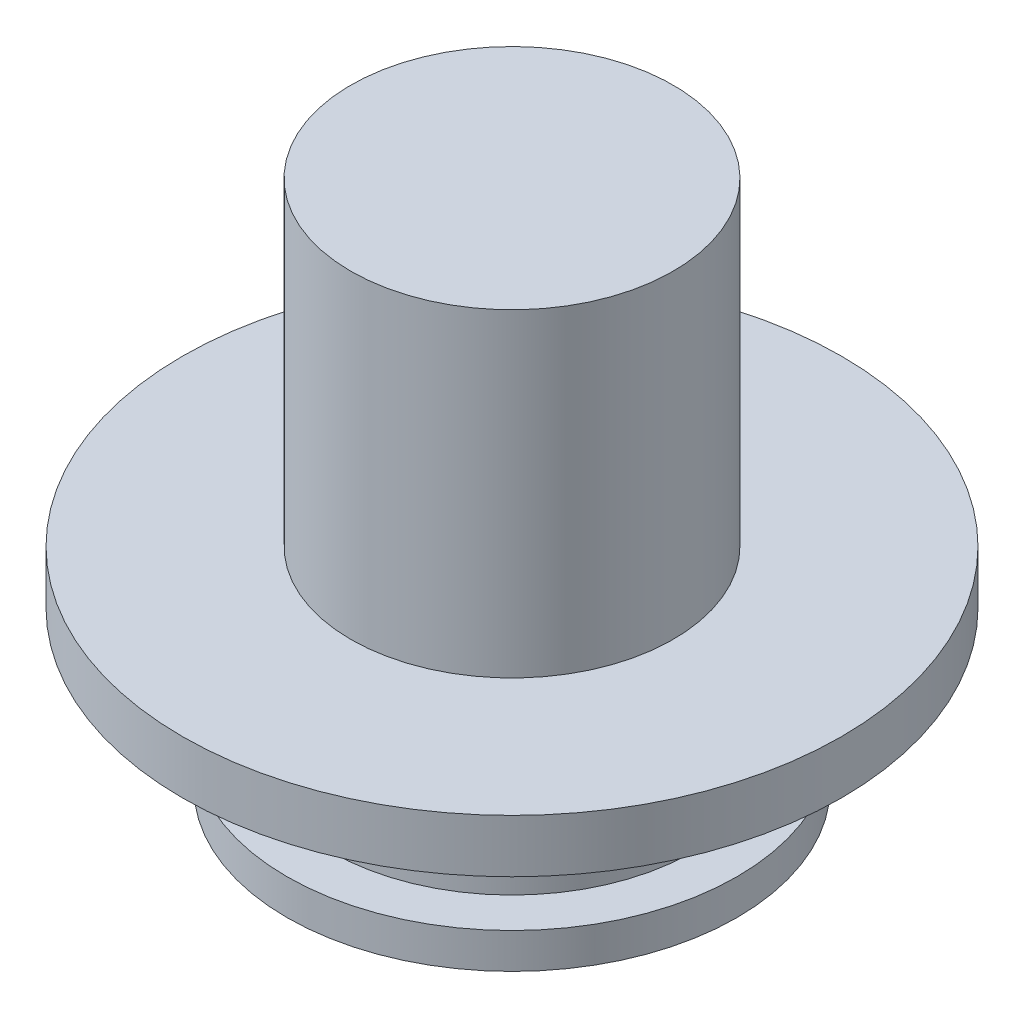
SolidWorks part; units mm, degrees
ref_plane "Front Plane" through (0, 0, 0) normal (0, 0, 1) x (1, 0, 0)
ref_plane "Top Plane" through (0, 0, 0) normal (0, 1, 0) x (1, 0, 0)
ref_plane "Right Plane" through (0, 0, 0) normal (1, 0, 0) x (0, 0, -1)
sketch "Sketch1" plane through (0, 0, 0) normal (0, 1, 0) x (1, 0, 0)
  circle A0 centre (0, 0) radius 6.35
  dimension "D1" = 12.7
extrude "Boss-Extrude1" add sketch "Sketch1" along normal blind 1
sketch "Sketch2" plane through (0, 1, 0) normal (0, 1, 0) x (1, 0, 0)
  line L0 (0, 0) -> (0, 5.1) construction
  line L1 (0, 5.1) -> (0.5, 5.1) construction
  line L2 (0.5, 5.1) -> (0.5, -5.1) construction
  line L3 (0.5, -5.1) -> (-0.5, -5.1) construction
  line L4 (0, 0) -> (5.1, 0) construction
  line L9 (5.1, 0) -> (5.1, -0.5) construction
  line L10 (5.1, -0.5) -> (-5.1, -0.5) construction
  line L11 (-5.1, -0.5) -> (-5.1, 0.5) construction
  circle A0 centre (0, 0) radius 5.1245
sketch "Sketch3" plane through (0, 4.4, 0) normal (0, 1, 0) x (1, 0, 0)
  circle A0 centre (0, 0) radius 9.3
extrude "Boss-Extrude3" add sketch "Sketch3" along normal blind 1.5
sketch "Sketch5" plane through (0, 5.9, 0) normal (0, 1, 0) x (1, 0, 0)
  circle A0 centre (0, 0) radius 4.55
  dimension "D1" = 9.1
extrude "Boss-Extrude4" add sketch "Sketch5" along normal blind 9
extrude "Boss-Extrude5" add sketch "Sketch2" along normal up to next
